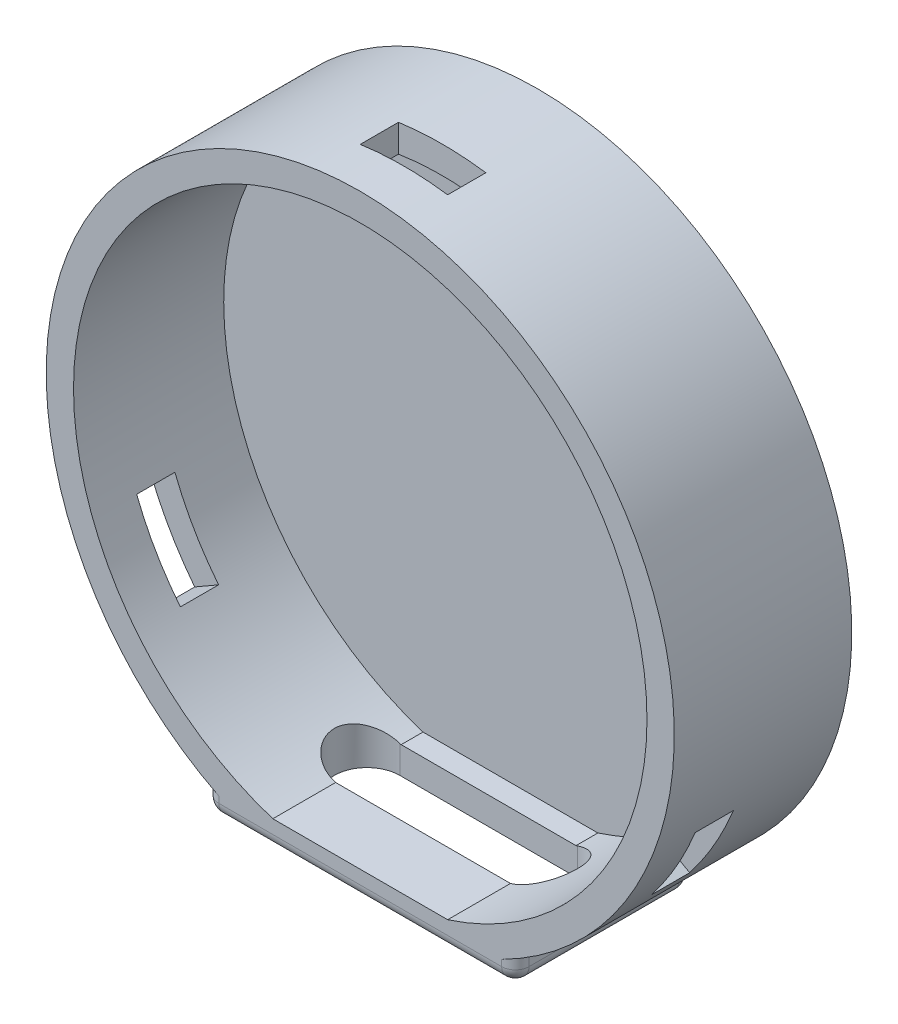
SolidWorks part; units mm, degrees
ref_plane "前视基准面" through (0, 0, 0) normal (0, 0, 1) x (1, 0, 0)
ref_plane "上视基准面" through (0, 0, 0) normal (0, 1, 0) x (1, 0, 0)
ref_plane "右视基准面" through (0, 0, 0) normal (1, 0, 0) x (0, 0, -1)
sketch "草图1" plane through (0, 0, 0) normal (0, 0, 1) x (1, 0, 0)
  circle A0 centre (0, 0) radius 11.5
  dimension "D1" = 23
extrude "凸台-拉伸1" add sketch "草图1" against normal blind 1
sketch "草图2" plane through (0, 0, 0) normal (0, 0, 1) x (1, 0, 0)
  circle A0 centre (0, 0) radius 10.5
  dimension "D1" = 21
extrude "拉伸-薄壁1" add sketch "草图2" along normal blind 5.5 thin
sketch "草图6" plane through (0, 0, 0) normal (0, 0, 1) x (1, 0, 0)
  line L0 (-6.25, -10) -> (6.25, -10)
  line L1 (6.25, -10) -> (6.25, -12.5)
  line L2 (6.25, -12.5) -> (-6.25, -12.5)
  line L3 (-6.25, -12.5) -> (-6.25, -10)
  point P1 (0, 0)
  point P6 (0, -10)
  point P9 (0, 0)
  point P11 (0, 0)
  dimension "D1" = 2.5
  dimension "D2" = 12.5
  dimension "D4" = 10
extrude "切除-拉伸2" cut sketch "草图6" against normal through all both and the other way through all
sketch "草图7" plane through (0, 0, 0) normal (0, 1, 0) x (1, 0, 0)
  line L1 (-5.6789, -5.5) -> (5.6789, -5.5)
  line L2 (-5.6789, -5.5) -> (-5.6789, 1)
  line L3 (-5.6789, 1) -> (5.6789, 1)
  line L4 (5.6789, -5.5) -> (5.6789, 1)
extrude "凸台-拉伸2" add sketch "草图7" against normal blind 1 from surface at -10 starting at face at (0, -10, 2.5)
sketch "草图3" plane through (0, 0, 0) normal (0, 1, 0) x (1, 0, 0)
  line L0 (-3.25, -2) -> (3.25, -2) construction
  line L1 (-3.25, -0.8) -> (3.25, -0.8)
  line L2 (-3.25, -3.2) -> (3.25, -3.2)
  line L4 (11.5, 1) -> (-11.5, 1) construction
  arc A0 (-3.25, -0.8) -> (-3.25, -3.2) centre (-3.25, -2) ccw
  arc A1 (3.25, -3.2) -> (3.25, -0.8) centre (3.25, -2) ccw
  point P2 (0, -2)
  point P7 (3.25, -2)
  point P8 (-3.25, -2)
  point P9 (0, 1)
  dimension "D1" = 1.2
  dimension "D2" = 6.5
  dimension "D3" = 3
extrude "切除-拉伸1" cut sketch "草图3" against normal through all
fillet "圆角2" radius 0.5 8 edges at (-5.6789, -10.5, -1) (5.6789, -10.5, -1) (0, -11, -1) (5.6789, -11, 2.25) (5.6789, -10.5, 5.5) (0, -11, 5.5) (-5.6789, -10.5, 5.5) (-5.6789, -11, 2.25)
sketch "草图9" plane through (0, 0, 0) normal (0, 1, 0) x (1, 0, 0)
  line L0 (-11.5, -5.5) -> (11.5, -5.5) construction
  line L1 (-1.6, -2.5) -> (1.6, -2.5)
  line L2 (-1.6, -2.5) -> (-1.6, -3.9)
  line L3 (-1.6, -3.9) -> (1.6, -3.9)
  line L4 (1.6, -2.5) -> (1.6, -3.9)
  line L5 (-1.6, -2.5) -> (1.6, -3.9) construction
  line L6 (-1.6, -3.9) -> (1.6, -2.5) construction
  point P0 (0, -3.2)
  dimension "D1" = 2.3
  dimension "D2" = 1.4
  dimension "D3" = 3.2
extrude "切除-拉伸3" cut sketch "草图9" along normal through all
pattern_circular "阵列(圆周)1" count 3 over 360 about axis through (0, 0, 0) along (0, 0, 1) of "切除-拉伸3"
